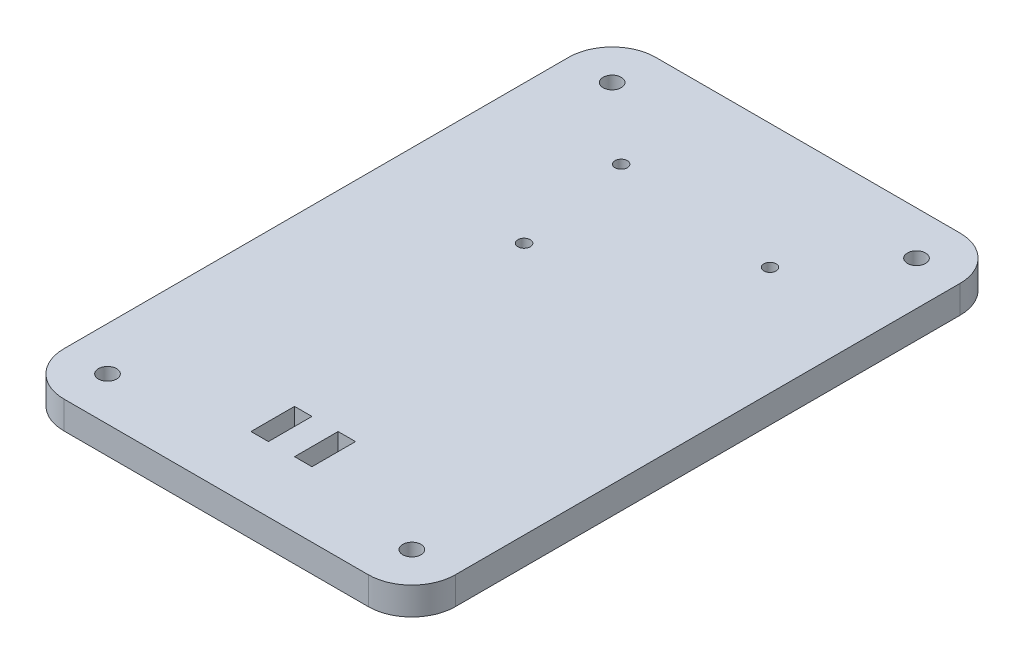
SolidWorks part; units mm, degrees
ref_plane "Front Plane" through (0, 0, 0) normal (0, 0, 1) x (1, 0, 0)
ref_plane "Top Plane" through (0, 0, 0) normal (0, 1, 0) x (1, 0, 0)
ref_plane "Right Plane" through (0, 0, 0) normal (1, 0, 0) x (0, 0, -1)
sketch "Sketch1" plane through (0, 0, 0) normal (0, 1, 0) x (1, 0, 0)
  line L0 (-25.146, 10.701) -> (-25.146, 47.912) construction
  line L1 (-34.925, -57.912) -> (34.925, -57.912) construction
  line L2 (-34.925, -57.912) -> (-34.925, 57.912) construction
  line L3 (-34.925, 57.912) -> (34.925, 57.912) construction
  line L4 (34.925, -57.912) -> (34.925, 57.912) construction
  line L5 (-34.925, -57.912) -> (34.925, 57.912) construction
  line L6 (-34.925, 57.912) -> (34.925, -57.912) construction
  line L7 (-25.146, 10.701) -> (25.146, 10.701) construction
  line L8 (25.146, 10.701) -> (25.146, 47.912) construction
  line L9 (-25.146, 47.912) -> (25.146, 47.912) construction
  line L10 (25.146, 10.701) -> (34.925, 10.701) construction
  line L11 (-34.925, 10.701) -> (-25.146, 10.701) construction
  line L12 (0, 57.912) -> (0, 67.912) construction
  line L13 (-34.925, -67.912) -> (34.925, -67.912)
  line L14 (-44.925, -57.912) -> (-44.925, 57.912)
  line L15 (-34.925, 67.912) -> (34.925, 67.912)
  line L16 (44.925, -57.912) -> (44.925, 57.912)
  line L17 (-44.925, -67.912) -> (44.925, 67.912) construction
  line L18 (-44.925, 67.912) -> (44.925, -67.912) construction
  line L19 (0, -67.912) -> (0, -57.912) construction
  line L20 (44.925, 0) -> (34.925, 0) construction
  line L21 (-44.925, 0) -> (-34.925, 0) construction
  line L22 (-3, -47.912) -> (3, -47.912) construction
  line L23 (-7, -42.912) -> (-3, -42.912)
  line L24 (-7, -42.912) -> (-7, -52.912)
  line L25 (-7, -52.912) -> (-3, -52.912)
  line L26 (-3, -42.912) -> (-3, -52.912)
  line L27 (-7, -42.912) -> (-3, -52.912) construction
  line L28 (-7, -52.912) -> (-3, -42.912) construction
  line L29 (3, -52.912) -> (7, -52.912)
  line L30 (3, -52.912) -> (3, -42.912)
  line L31 (3, -42.912) -> (7, -42.912)
  line L32 (7, -52.912) -> (7, -42.912)
  line L33 (3, -52.912) -> (7, -42.912) construction
  line L34 (3, -42.912) -> (7, -52.912) construction
  line L35 (0, -57.912) -> (0, -47.912) construction
  circle A0 centre (-34.925, 57.912) radius 2.0828
  circle A1 centre (34.925, 57.912) radius 2.0828
  circle A2 centre (34.925, -57.912) radius 2.0828
  circle A3 centre (-34.925, -57.912) radius 2.0828
  circle A4 centre (19.939, 39.276) radius 1.4224
  circle A5 centre (-13.081, 15.8572) radius 1.4224
  circle A6 centre (-17.653, 42.705) radius 1.4224
  arc A7 (34.925, 67.912) -> (44.925, 57.912) centre (34.925, 57.912) cw
  arc A8 (44.925, -57.912) -> (34.925, -67.912) centre (34.925, -57.912) cw
  arc A9 (-34.925, -67.912) -> (-44.925, -57.912) centre (-34.925, -57.912) cw
  arc A10 (-34.925, 67.912) -> (-44.925, 57.912) centre (-34.925, 57.912) ccw
  point P0 (0, 0)
  point P21 (0, 0)
  point P47 (-5, -47.912)
  point P52 (5, -47.912)
  point P59 (0, -47.912)
  dimension "D1" = 4.1656
  dimension "D12" = 2.8448
  dimension "D16" = 10
  dimension "D2" = 69.85
  dimension "D3" = 115.824
  dimension "D4" = 37.211
  dimension "D5" = 50.292
  dimension "D6" = 45.085
  dimension "D7" = 28.575
  dimension "D8" = 12.065
  dimension "D9" = 5.1562
  dimension "D10" = 32.004
  dimension "D11" = 7.493
  dimension "D13" = 10
  dimension "D14" = 10
  dimension "D15" = 10
  dimension "D17" = 4
  dimension "D18" = 10
  dimension "D19" = 10
  dimension "D20" = 6
extrude "Boss-Extrude1" add sketch "Sketch1" along normal blind 6.35
